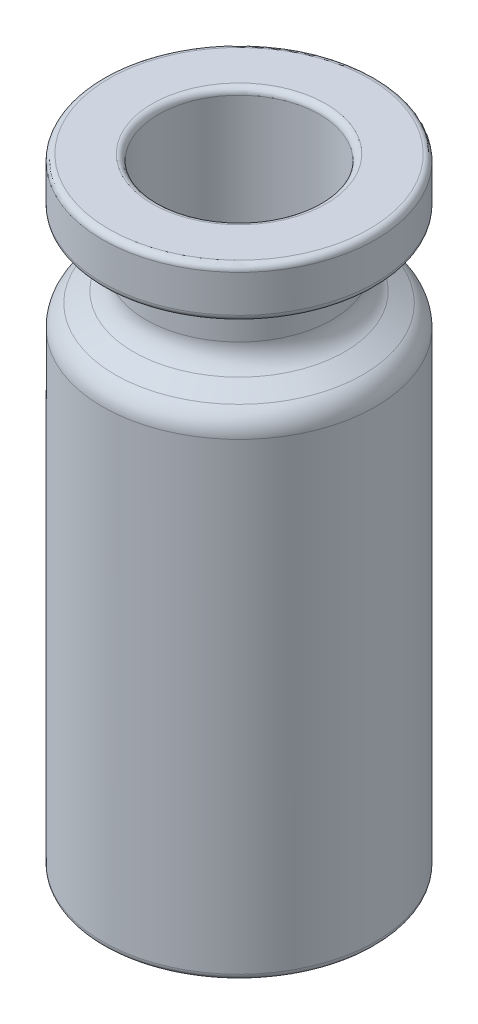
SolidWorks part; units mm, degrees
ref_plane "Front Plane" through (0, 0, 0) normal (0, 0, 1) x (1, 0, 0)
ref_plane "Top Plane" through (0, 0, 0) normal (0, 1, 0) x (1, 0, 0)
ref_plane "Right Plane" through (0, 0, 0) normal (1, 0, 0) x (0, 0, -1)
sketch "Sketch1" plane through (0, 0, 0) normal (0, 0, 1) x (1, 0, 0)
  line L0 (0, 0) -> (11, 0)
  line L1 (11, 0) -> (11, 50) construction
  line L2 (11, 0) -> (11, 39)
  line L3 (11, 39) -> (7.5, 41)
  line L4 (7.5, 41) -> (7.5, 46)
  line L5 (7.5, 46) -> (11, 46)
  line L6 (11, 46) -> (11, 50)
  line L7 (11, 50) -> (6.5, 50)
  line L8 (6.5, 50) -> (6.5, 40.4197)
  line L9 (6.5, 40.4197) -> (10, 38.4197)
  line L10 (10, 38.4197) -> (10, 1)
  line L11 (10, 1) -> (0, 1)
  line L12 (0, 1) -> (0, 0)
  line L13 (0, 0) -> (0, 50) construction
  line L14 (0, 50) -> (6.5, 50) construction
  dimension "D1" = 11
  dimension "D2" = 50
  dimension "D3" = 4
  dimension "D4" = 15
  dimension "D5" = 1
  dimension "D6" = 1
  dimension "D7" = 1
  dimension "D8" = 1
  dimension "D9" = 5
  dimension "D10" = 39
revolve "Revolve1" add sketch "Sketch1" angle 360 about L13
fillet "Fillet1" radius 2 3 edges at (0, 46, -7.5) (0, 41, -7.5) (0, 39, -11)
fillet "Fillet2" radius 0.5 4 edges at (0, 50, -6.5) (0, 46, -11) (0, 50, -11) (0, 0, -11)
